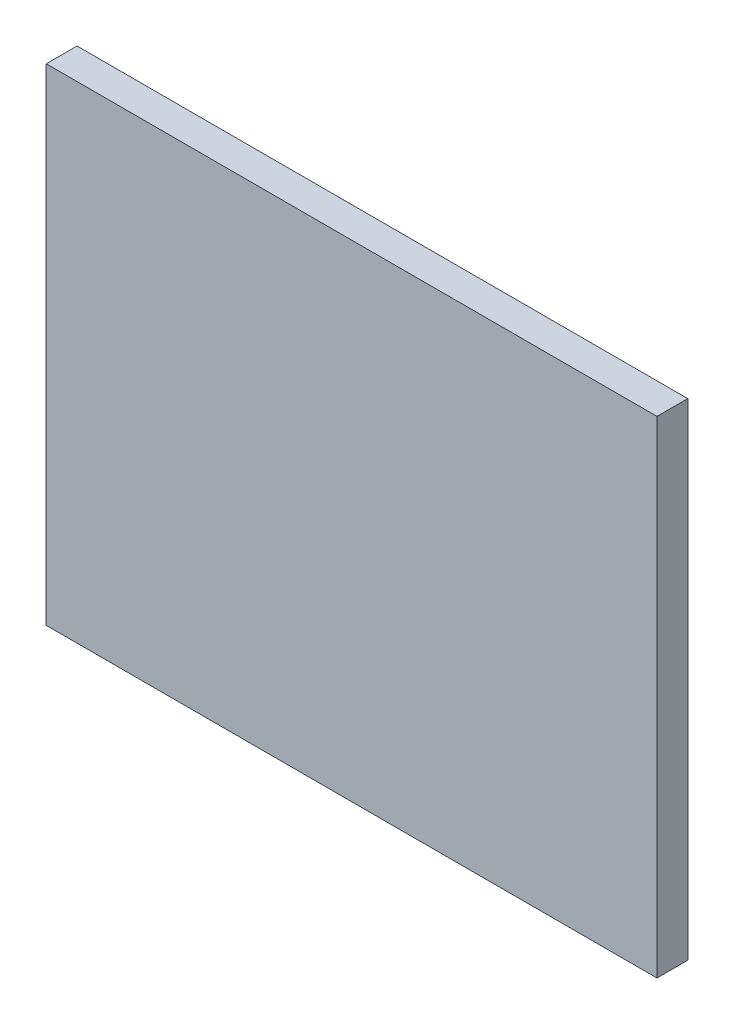
SolidWorks part; units mm, degrees
ref_plane "前视基准面" through (0, 0, 0) normal (0, 0, 1) x (1, 0, 0)
ref_plane "上视基准面" through (0, 0, 0) normal (0, 1, 0) x (1, 0, 0)
ref_plane "右视基准面" through (0, 0, 0) normal (1, 0, 0) x (0, 0, -1)
other "Configuration Table"
sketch "草图1" plane through (0, 0, 0) normal (0, 0, 1) x (1, 0, 0)
  line L1 (-60, -39.5) -> (60, -39.5)
  line L2 (-60, -39.5) -> (-60, 39.5)
  line L3 (-60, 39.5) -> (60, 39.5)
  line L4 (60, -39.5) -> (60, 39.5)
  line L5 (-60, -39.5) -> (60, 39.5) construction
  line L6 (-60, 39.5) -> (60, -39.5) construction
  point P0 (0, 0)
  dimension "D1" = 79
  dimension "D2" = 120
extrude "凸台-拉伸1" add sketch "草图1" along normal blind 5
sketch "草图2" plane through (0, 0, 0) normal (0, 0, -1) x (-1, 0, 0)
  line L0 (-60, 39.5) -> (60, 39.5) construction
  line L1 (-60, -39.5) -> (-39.1978, -39.5)
  line L2 (-60, -39.5) -> (-60, 39.5)
  line L3 (-60, 39.5) -> (-39.1978, 39.5)
  line L4 (-39.1978, -39.5) -> (-39.1978, 39.5)
extrude "切除-拉伸1" cut sketch "草图2" against normal blind 8
